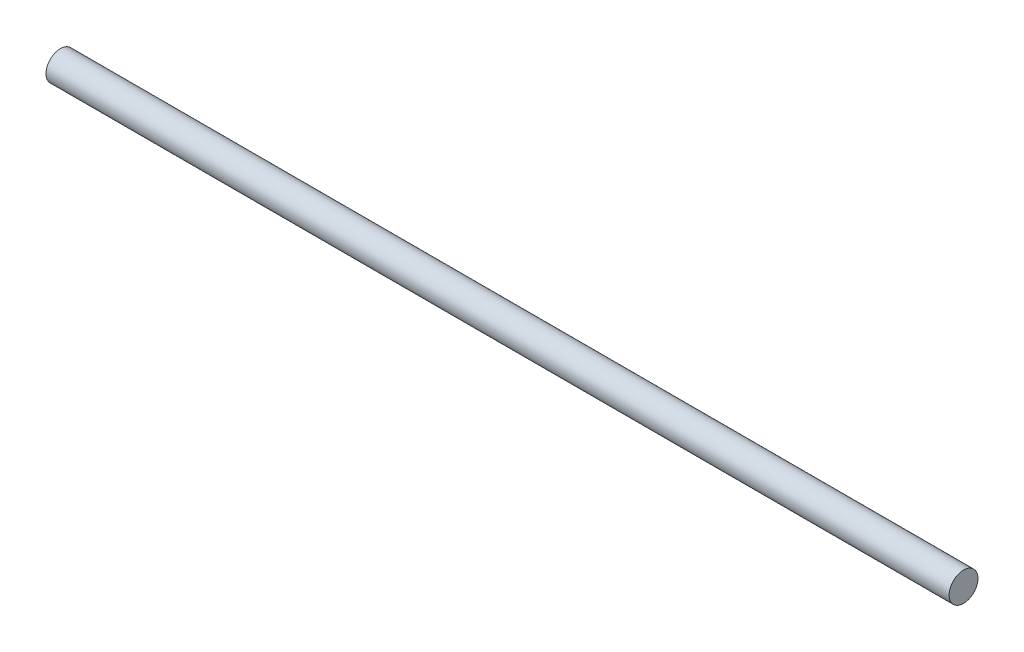
SolidWorks part; units mm, degrees
ref_plane "前视基准面" through (0, 0, 0) normal (0, 0, 1) x (1, 0, 0)
ref_plane "上视基准面" through (0, 0, 0) normal (0, 1, 0) x (1, 0, 0)
ref_plane "右视基准面" through (0, 0, 0) normal (1, 0, 0) x (0, 0, -1)
sketch "草图1" plane through (0, 0, 0) normal (1, 0, 0) x (0, 0, -1)
  circle A0 centre (0, 0) radius 4
  dimension "D1" = 8
extrude "凸台-拉伸1" add sketch "草图1" along normal blind 250
